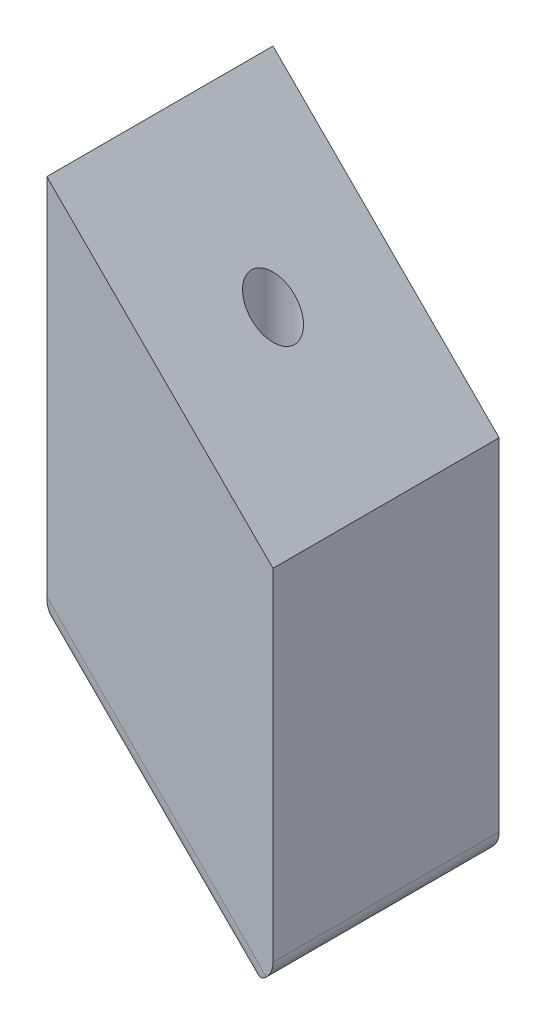
SolidWorks part; units mm, degrees
ref_plane "Front Plane" through (0, 0, 0) normal (0, 0, 1) x (1, 0, 0)
ref_plane "Top Plane" through (0, 0, 0) normal (0, 1, 0) x (1, 0, 0)
ref_plane "Right Plane" through (0, 0, 0) normal (1, 0, 0) x (0, 0, -1)
sketch "Sketch1" plane through (0, 0, 0) normal (0, 1, 0) x (1, 0, 0)
  line L1 (-10, -10) -> (10, -10)
  line L2 (-10, -10) -> (-10, 10)
  line L3 (-10, 10) -> (10, 10)
  line L4 (10, -10) -> (10, 10)
  line L5 (-10, -10) -> (10, 10) construction
  line L6 (-10, 10) -> (10, -10) construction
  point P0 (0, 0)
  dimension "D1" = 20
extrude "Boss-Extrude1" add sketch "Sketch1" along normal blind 15
sketch "Sketch2" plane through (0, 0, 10) normal (0, 0, 1) x (1, 0, 0)
  line L0 (10, 15) -> (-10, 35)
  line L1 (-10, 35) -> (-10, 15)
  line L2 (-10, 0) -> (10, -20)
  line L3 (10, -20) -> (10, 0)
  line L6 (-10, 15) -> (10, 15) construction
  line L7 (-10, 15) -> (10, 15)
  line L8 (-10, 0) -> (10, 0)
extrude "Boss-Extrude2" add sketch "Sketch2" against normal up to surface (20 mm away) up to face at (0, 7.5, -10)
sketch "Sketch3" plane through (0, 0, -10) normal (0, 0, -1) x (-1, 0, 0)
  line L0 (-5, -15) -> (-5, -5)
  line L1 (-10, -20) -> (10, 0) construction
  line L2 (-5, -5) -> (5, -5)
  line L4 (-10, 15) -> (-10, -20) construction
  line L6 (-5, -15) -> (5, -5)
  dimension "D1" = 5
  dimension "D2" = 5
extrude "Cut-Extrude1" cut sketch "Sketch3" against normal through all
sketch "Sketch4" plane through (0, -5, 0) normal (0, -1, 0) x (1, 0, 0)
  circle A0 centre (0, 0) radius 1.905
  dimension "D1" = 3.81
extrude "Cut-Extrude2" cut sketch "Sketch4" against normal through all
sketch "Sketch5" plane through (0, 0, 10) normal (0, 0, 1) x (1, 0, 0)
  line L0 (5, -5) -> (5, -15)
  line L1 (5, -15) -> (-5, -5)
  line L2 (-5, -5) -> (5, -5)
extrude "Boss-Extrude3" add sketch "Sketch5" against normal blind 4
sketch "Sketch6" plane through (0, 0, -10) normal (0, 0, -1) x (-1, 0, 0)
  line L3 (5, -5) -> (-5, -5)
  line L4 (-5, -5) -> (-5, -15)
  line L5 (-5, -15) -> (5, -5)
  line L6 (5, -5) -> (-5, -5)
  line L7 (-5, -5) -> (-5, -15)
  line L8 (-5, -15) -> (5, -5)
  dimension "D1" = 0
extrude "Boss-Extrude4" add sketch "Sketch6" against normal blind 4
fillet "Fillet1" radius 2 4 edges at (10, -20, 0) (0, -10, -10) (0, -10, 10) (-10, 0, 0)
